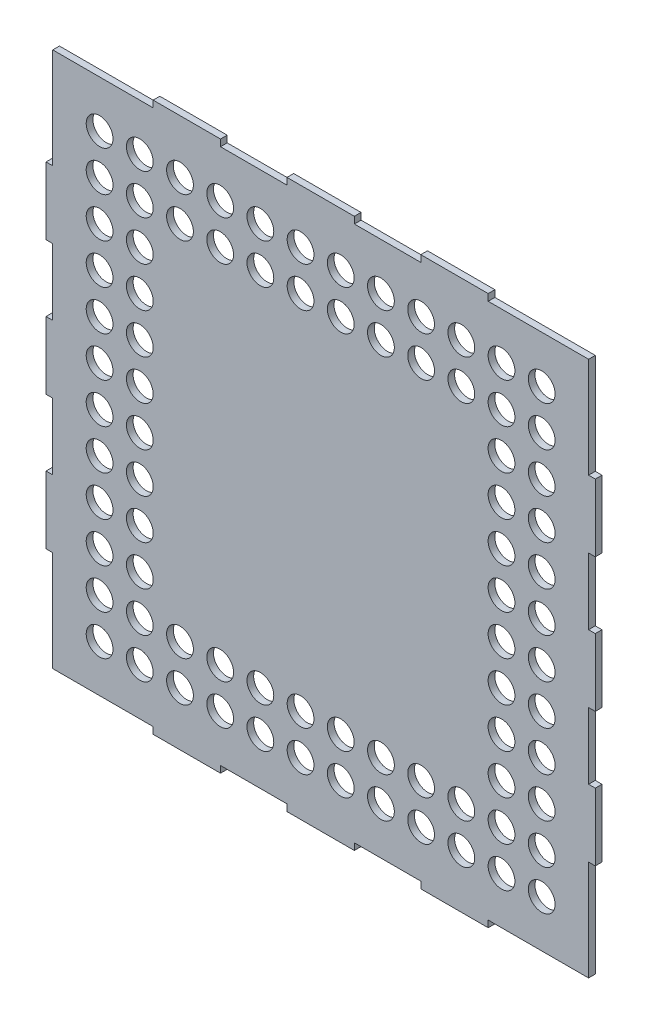
SolidWorks part; units mm, degrees
ref_plane "Ebene vorne" through (0, 0, 0) normal (0, 0, 1) x (1, 0, 0)
ref_plane "Ebene oben" through (0, 0, 0) normal (0, 1, 0) x (1, 0, 0)
ref_plane "Ebene rechts" through (0, 0, 0) normal (1, 0, 0) x (0, 0, -1)
sketch "Skizze1" plane through (0, 0, 0) normal (0, 0, 1) x (1, 0, 0)
  line L1 (0, 0) -> (410, 0)
  line L2 (0, 0) -> (0, 410)
  line L3 (0, 410) -> (410, 410)
  line L4 (410, 0) -> (410, 410)
  dimension "D1" = 410
  dimension "D2" = 410
extrude "Aufsatz-Linear austragen1" add sketch "Skizze1" along normal blind 5 contours L2 L3 L4 L1
sketch "Skizze2" plane through (0, 0, 5) normal (0, 0, 1) x (1, 0, 0)
  line L0 (0, 410) -> (410, 410) construction
  line L1 (-92.7967, 379.65) -> (5, 379.65)
  line L2 (-92.7967, 379.65) -> (-92.7967, 330.05)
  line L3 (-92.7967, 330.05) -> (5, 330.05)
  line L4 (5, 379.65) -> (5, 330.05)
  dimension "D1" = 49.6
  dimension "D2" = 5
  dimension "D3" = 79.95
extrude "Schnitt-Linear austragen1" cut sketch "Skizze2" against normal blind 5
pattern_linear "Lineares Muster1" count 4 spacing 99.9 along (0, -1, 0) of "Schnitt-Linear austragen1"
ref_plane "Ebene1" through (205, 0, 0) normal (1, 0, 0) x (0, 0, -1)
mirror "Spiegeln1" about plane through (205, 0, 0) normal (1, 0, 0) of "Schnitt-Linear austragen1", "Lineares Muster1"
sketch "Skizze3" plane through (0, 0, 5) normal (0, 0, 1) x (1, 0, 0)
  line L0 (0, 410) -> (410, 410) construction
  line L1 (30.35, 446.7791) -> (79.95, 446.7791)
  line L2 (30.35, 446.7791) -> (30.35, 405)
  line L3 (30.35, 405) -> (79.95, 405)
  line L4 (79.95, 446.7791) -> (79.95, 405)
  dimension "D1" = 49.6
  dimension "D2" = 5
  dimension "D3" = 79.95
extrude "Schnitt-Linear austragen2" cut sketch "Skizze3" against normal blind 5
pattern_linear "Lineares Muster2" count 4 spacing 99.9 along (1, 0, 0) of "Schnitt-Linear austragen2"
ref_plane "Ebene2" through (0, 205, 0) normal (0, 1, 0) x (1, 0, 0)
mirror "Spiegeln2" about plane through (0, 205, 0) normal (0, 1, 0) of "Schnitt-Linear austragen2", "Lineares Muster2"
sketch "Skizze4" plane through (0, 0, 5) normal (0, 0, 1) x (1, 0, 0)
  line L0 (5, 379.65) -> (5, 405)
  line L1 (30.35, 405) -> (5, 405)
  line L7 (5, 379.65) -> (-47.8629, 379.65)
  line L10 (-47.8629, 379.65) -> (-47.8629, 405)
  line L12 (-47.8629, 405) -> (-47.8629, 431.5498)
  line L13 (-47.8629, 431.5498) -> (5, 431.5498)
  line L17 (5, 431.5498) -> (30.35, 431.5498)
  line L18 (30.35, 405) -> (30.35, 431.5498)
extrude "Schnitt-Linear austragen3" cut sketch "Skizze4" against normal blind 5
mirror "Spiegeln3" about plane through (205, 0, 0) normal (1, 0, 0) of "Schnitt-Linear austragen3"
mirror "Spiegeln4" about plane through (0, 205, 0) normal (0, 1, 0) of "Schnitt-Linear austragen3", "Spiegeln3"
sketch "Skizze5" plane through (0, 0, 5) normal (0, 0, 1) x (1, 0, 0)
  line L1 (48.3367, 321.7639) -> (368.3367, 321.7639) construction
  line L2 (48.3367, 321.7639) -> (48.3367, 141.7639) construction
  line L3 (48.3367, 141.7639) -> (368.3367, 141.7639) construction
  line L4 (368.3367, 321.7639) -> (368.3367, 141.7639) construction
  circle A0 centre (40, 370) radius 10
  dimension "D3" = 20
  dimension "D1" = 320
  dimension "D2" = 180
  dimension "D4" = 35
  dimension "D5" = 35
extrude "Schnitt-Linear austragen4" cut sketch "Skizze5" against normal blind 5 contours A0
pattern_linear "Lineares Muster3" count 12 spacing 30 along (1, 0, 0) count 12 spacing 30 along (0, -1, 0) skipping (2, 2), (2, 3), (2, 4), (2, 5), (2, 6), (2, 7), (2, 8), (2, 9), (3, 2), (3, 3), (3, 4), (3, 5), (3, 6), (3, 7), (3, 8), (3, 9), (4, 2), (4, 3), (4, 4), (4, 5), (4, 6), (4, 7), (4, 8), (4, 9), (5, 2), (5, 3), (5, 4), (5, 5), (5, 6), (5, 7), (5, 8), (5, 9), (6, 2), (6, 3), (6, 4), (6, 5), (6, 6), (6, 7), (6, 8), (6, 9), (7, 2), (7, 3), (7, 4), (7, 5), (7, 6), (7, 7), (7, 8), (7, 9), (8, 2), (8, 3), (8, 4), (8, 5), (8, 6), (8, 7), (8, 8), (8, 9), (9, 2), (9, 3), (9, 4), (9, 5), (9, 6), (9, 7), (9, 8), (9, 9) of "Schnitt-Linear austragen4"
pattern_linear "Lineares Muster4" [suppressed] count 2 spacing 320
pattern_linear "Lineares Muster5" [suppressed] count 10 spacing 30 count 2 spacing 30
